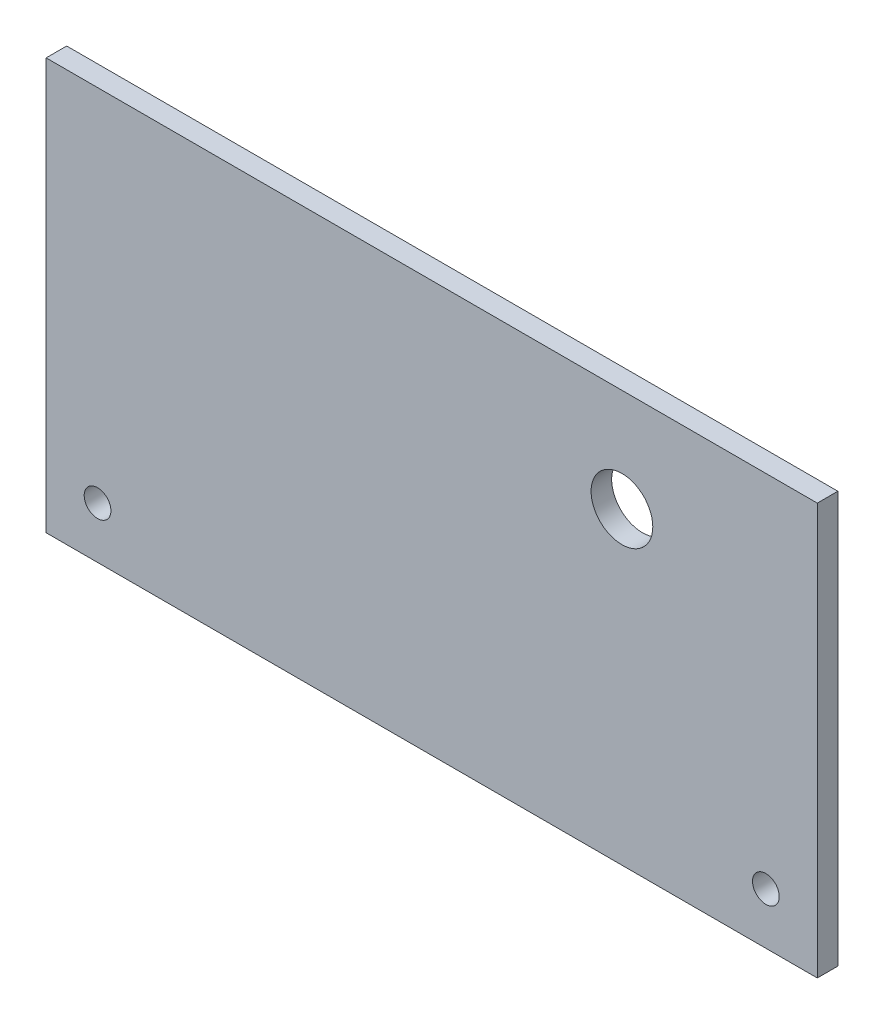
SolidWorks part; units mm, degrees
ref_plane "前视基准面" through (0, 0, 0) normal (0, 0, 1) x (1, 0, 0)
ref_plane "上视基准面" through (0, 0, 0) normal (0, 1, 0) x (1, 0, 0)
ref_plane "右视基准面" through (0, 0, 0) normal (1, 0, 0) x (0, 0, -1)
sketch "草图1" plane through (0, 0, 0) normal (0, 0, 1) x (1, 0, 0)
  line L1 (-63.1554, 36.0621) -> (86.8446, 36.0621)
  line L2 (-63.1554, 36.0621) -> (-63.1554, -43.9379)
  line L3 (-63.1554, -43.9379) -> (86.8446, -43.9379)
  line L4 (86.8446, 36.0621) -> (86.8446, -43.9379)
  dimension "D1" = 150
  dimension "D2" = 80
extrude "凸台-拉伸1" add sketch "草图1" along normal blind 4
sketch "草图2" plane through (0, 0, 4) normal (0, 0, 1) x (1, 0, 0)
  circle A0 centre (48.8446, 16.0621) radius 6
  circle A1 centre (-53.1554, -33.9379) radius 2.6
  circle A2 centre (76.8446, -33.9379) radius 2.6
  dimension "D1" = 12
  dimension "D2" = 5.2
  dimension "D3" = 5.2
extrude "切除-拉伸2" cut sketch "草图2" along normal blind 12 and the other way blind 27
